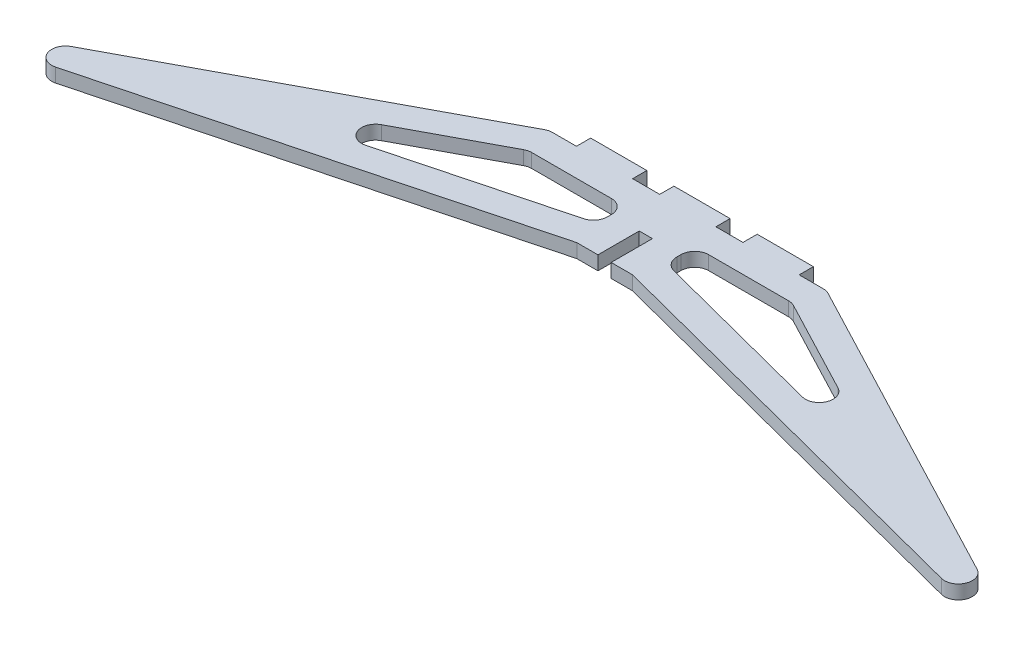
SolidWorks part; units mm, degrees
ref_plane "Front Plane" through (0, 0, 0) normal (0, 0, 1) x (1, 0, 0)
ref_plane "Top Plane" through (0, 0, 0) normal (0, 1, 0) x (1, 0, 0)
ref_plane "Right Plane" through (0, 0, 0) normal (1, 0, 0) x (0, 0, -1)
sketch "Sketch2" plane through (0, 0, 0) normal (0, 1, 0) x (1, 0, 0)
  line L5 (-1.5113, -19.05) -> (-1.5113, -9.6012)
  line L6 (-1.5113, -9.6012) -> (1.5113, -9.6012)
  line L7 (1.5113, -9.6012) -> (1.5113, -19.05)
  line L8 (12.6238, 3.2512) -> (12.6238, 0)
  line L9 (-6.4262, 3.2512) -> (-6.4262, 0)
  line L10 (6.4262, 3.2512) -> (6.4262, 0)
  line L12 (-12.6238, 0) -> (-6.4262, 0)
  line L13 (25.4762, 0) -> (30.968, 0)
  line L14 (6.4262, 3.2512) -> (-6.4262, 3.2512)
  line L15 (-52.0834, -18.0412) -> (-30.8629, -6.7235)
  line L16 (-25.4762, 3.2512) -> (-25.4762, 0)
  line L17 (-25.4762, 0) -> (-30.9562, 0)
  line L18 (-103.0239, -38.0127) -> (-32.4504, -0.3735)
  line L19 (-100.7218, -43.8847) -> (-6.35, -19.05)
  line L20 (-6.35, -19.05) -> (-1.5113, -19.05)
  line L21 (12.6238, 3.2512) -> (25.4762, 3.2512)
  line L22 (32.4425, -0.3632) -> (104.1649, -37.9739)
  line L23 (6.35, -19.05) -> (101.8924, -43.8589)
  line L24 (-12.6238, 3.2512) -> (-12.6238, 0)
  line L25 (25.4762, 3.2512) -> (25.4762, 0)
  line L26 (6.4262, 0) -> (12.6238, 0)
  line L27 (1.5113, -19.05) -> (6.35, -19.05)
  line L29 (-49.7813, -23.9131) -> (-10.3224, -13.5292)
  line L30 (-7.9554, -10.4725) -> (-7.9514, -9.5388)
  line L31 (7.9416, -9.5291) -> (7.9428, -10.4512)
  line L32 (10.3198, -13.5202) -> (50.0257, -23.8304)
  line L33 (30.8786, -6.7132) -> (52.2982, -17.9455)
  line L34 (-12.6238, 3.2512) -> (-25.4762, 3.2512)
  line L38 (-11.1263, -6.35) -> (-29.3688, -6.35)
  line L39 (11.1166, -6.35) -> (29.4041, -6.35)
  arc A0 (-100.7218, -43.8847) -> (-103.0239, -38.0127) centre (-101.5298, -40.8142) cw
  arc A1 (101.8924, -43.8589) -> (104.1649, -37.9739) centre (102.6904, -40.7858) ccw
  arc A2 (-30.9562, 0) -> (-32.4504, -0.3735) centre (-30.9562, -3.175) ccw
  arc A3 (30.968, 0) -> (32.4425, -0.3632) centre (30.968, -3.175) cw
  arc A4 (30.8786, -6.7132) -> (29.4041, -6.35) centre (29.4041, -9.525) ccw
  arc A5 (7.9416, -9.5291) -> (11.1166, -6.35) centre (11.1166, -9.525) cw
  arc A6 (-29.3688, -6.35) -> (-30.8629, -6.7235) centre (-29.3688, -9.525) ccw
  arc A7 (-7.9514, -9.5388) -> (-11.1263, -6.35) centre (-11.1263, -9.525) ccw
  arc A8 (-10.3224, -13.5292) -> (-7.9554, -10.4725) centre (-11.1304, -10.4587) ccw
  arc A9 (10.3198, -13.5202) -> (7.9428, -10.4512) centre (11.1178, -10.4471) cw
  arc A10 (50.0257, -23.8304) -> (52.2982, -17.9455) centre (50.8237, -20.7573) ccw
  arc A11 (-49.7813, -23.9131) -> (-52.0834, -18.0412) centre (-50.5893, -20.8426) cw
  dimension "D1" = 3.175
  dimension "D2" = 3.175
extrude "Boss-Extrude1" add sketch "Sketch2" along normal blind 3.175
